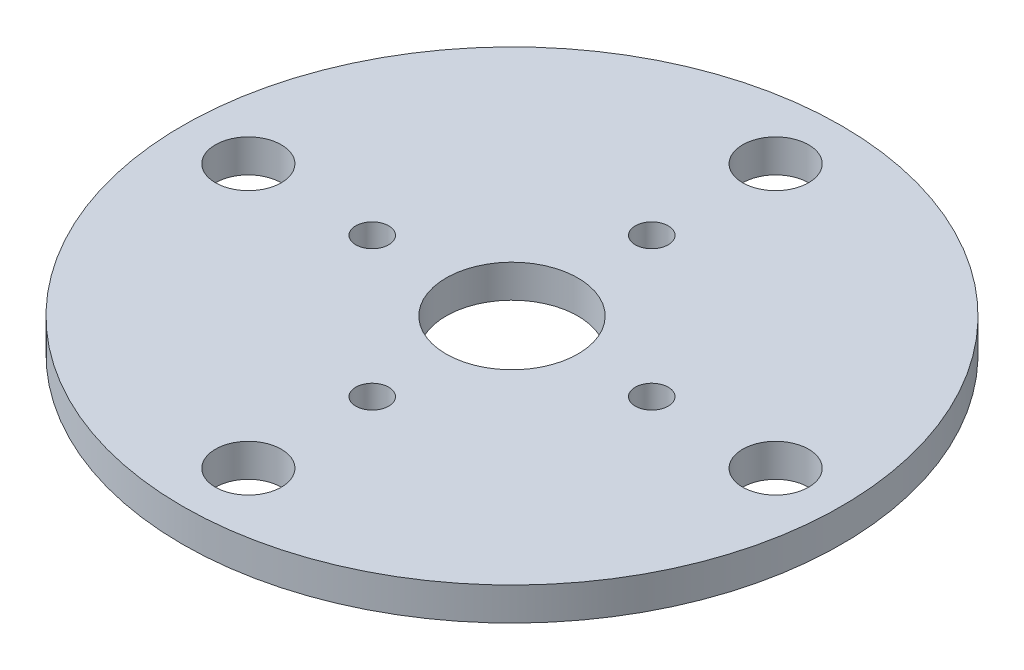
SolidWorks part; units mm, degrees
ref_plane "Front Plane" through (0, 0, 0) normal (0, 0, 1) x (1, 0, 0)
ref_plane "Top Plane" through (0, 0, 0) normal (0, 1, 0) x (1, 0, 0)
ref_plane "Right Plane" through (0, 0, 0) normal (1, 0, 0) x (0, 0, -1)
sketch "Sketch1" plane through (0, 0, 0) normal (0, 1, 0) x (1, 0, 0)
  line L6 (-10, 0) -> (0, 0) construction
  circle A0 centre (0, 0) radius 10
  circle A1 centre (0, 0) radius 2
  circle A2 centre (-8, 0) radius 1
  circle A3 centre (-4.241, 0) radius 0.5
  circle A4 centre (0, -4.241) radius 0.5
  circle A5 centre (0, -8) radius 1
  circle A6 centre (4.241, 0) radius 0.5
  circle A7 centre (8, 0) radius 1
  circle A8 centre (0, 4.241) radius 0.5
  circle A9 centre (0, 8) radius 1
  dimension "D1" = 20
  dimension "D2" = 4
  dimension "D3" = 2
  dimension "D4" = 1
  dimension "D5" = 8
  dimension "D6" = 8
  dimension "D7" = 8
  dimension "D8" = 8
extrude "Boss-Extrude1" add sketch "Sketch1" along normal blind 1
